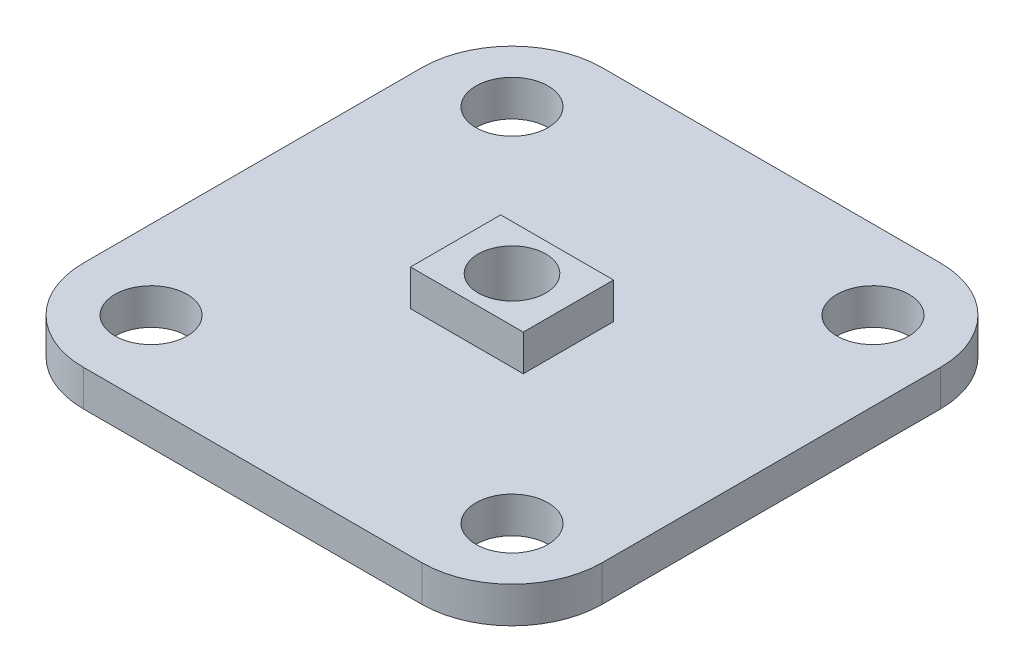
SolidWorks part; units mm, degrees
ref_plane "前视基准面" through (0, 0, 0) normal (0, 0, 1) x (1, 0, 0)
ref_plane "上视基准面" through (0, 0, 0) normal (0, 1, 0) x (1, 0, 0)
ref_plane "右视基准面" through (0, 0, 0) normal (1, 0, 0) x (0, 0, -1)
other "Configuration Table"
sketch "草图1" plane through (0, 0, 0) normal (0, 1, 0) x (1, 0, 0)
  line L1 (-11.5, -11.5) -> (11.5, -11.5)
  line L2 (-11.5, -11.5) -> (-11.5, 11.5)
  line L3 (-11.5, 11.5) -> (11.5, 11.5)
  line L4 (11.5, -11.5) -> (11.5, 11.5)
  line L5 (-11.5, -11.5) -> (11.5, 11.5) construction
  line L6 (-11.5, 11.5) -> (11.5, -11.5) construction
  point P0 (0, 0)
  dimension "D1" = 23
  dimension "D2" = 23
extrude "凸台-拉伸1" add sketch "草图1" along normal blind 1.6
sketch "草图2" plane through (0, 1.6, 0) normal (0, 1, 0) x (1, 0, 0)
  line L1 (-2.5, -2) -> (2.5, -2)
  line L2 (-2.5, -2) -> (-2.5, 2)
  line L3 (-2.5, 2) -> (2.5, 2)
  line L4 (2.5, -2) -> (2.5, 2)
  line L5 (-2.5, -2) -> (2.5, 2) construction
  line L6 (-2.5, 2) -> (2.5, -2) construction
  point P0 (0, 0)
  dimension "D1" = 5
  dimension "D2" = 4
extrude "凸台-拉伸2" add sketch "草图2" along normal blind 1.6
fillet "圆角1" radius 4 4 edges at (11.5, 0.8, -11.5) (-11.5, 0.8, -11.5) (11.5, 0.8, 11.5) (-11.5, 0.8, 11.5)
sketch "草图3" plane through (0, 0, 0) normal (0, -1, 0) x (1, 0, 0)
  line L1 (-8, -8) -> (8, -8) construction
  line L2 (-8, -8) -> (-8, 8) construction
  line L3 (-8, 8) -> (8, 8) construction
  line L4 (8, -8) -> (8, 8) construction
  line L5 (-8, -8) -> (8, 8) construction
  line L6 (-8, 8) -> (8, -8) construction
  circle A0 centre (-8, 8) radius 1.6
  circle A1 centre (8, 8) radius 1.6
  circle A2 centre (8, -8) radius 1.6
  circle A3 centre (-8, -8) radius 1.6
  point P0 (0, 0)
  point P16 (0, 0)
  dimension "D3" = 3.2
  dimension "D1" = 16
  dimension "D2" = 16
  dimension "D4" = 4
extrude "切除-拉伸1" cut sketch "草图3" against normal up to next
sketch "草图4" plane through (0, 0, 0) normal (0, -1, 0) x (1, 0, 0)
  circle A0 centre (0, 0) radius 1.5
  dimension "D1" = 3
extrude "切除-拉伸2" cut sketch "草图4" against normal up to next
